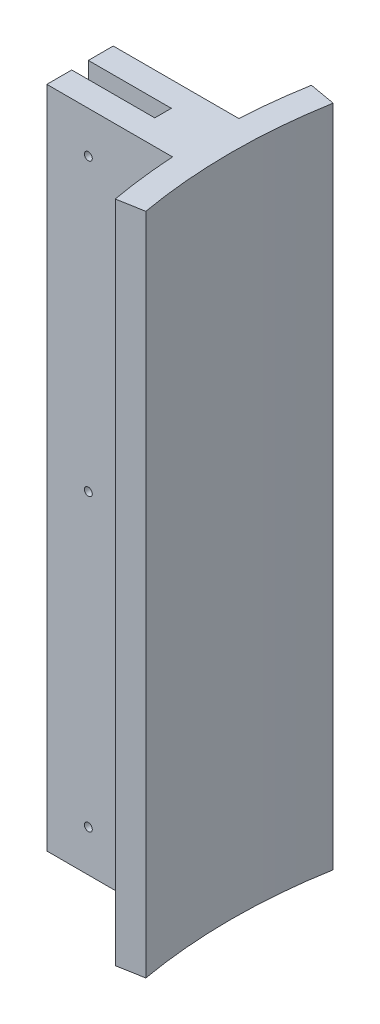
SolidWorks part; units mm, degrees
ref_plane "Front Plane" through (0, 0, 0) normal (0, 0, 1) x (1, 0, 0)
ref_plane "Top Plane" through (0, 0, 0) normal (0, 1, 0) x (1, 0, 0)
ref_plane "Right Plane" through (0, 0, 0) normal (1, 0, 0) x (0, 0, -1)
sketch "Sketch1" plane through (0, 0, 0) normal (0, 1, 0) x (1, 0, 0)
  line L0 (-65, 0) -> (0, 0) construction
  line L5 (-64.0125, -11.2871) -> (-67.1405, -11.8387)
  line L7 (0, 0) -> (-80.1235, 0) construction
  line L8 (-68.2228, -4) -> (-68.0775, -4)
  line L11 (-68.2228, -4) -> (-83.2228, -4)
  line L12 (-83.2228, 4) -> (-83.2228, 1)
  line L13 (-68.2228, 4) -> (-68.0937, 4)
  line L14 (-68.2228, 4) -> (-83.2228, 4)
  line L15 (-83.2228, 1) -> (-73.2228, 1)
  line L16 (-83.2228, -1) -> (-73.2228, -1)
  line L17 (-73.2228, -1) -> (-73.2228, 1)
  line L18 (-83.2228, -1) -> (-83.2228, -4)
  line L20 (-64.0125, 11.2871) -> (-67.1878, 11.847)
  arc A0 (-64.0125, -11.2871) -> (-64.0125, 11.2871) centre (0, 0) cw
  arc A3 (-67.1405, -11.8387) -> (-68.0775, -4) centre (-0.2035, 0.1379) cw
  arc A4 (-68.0937, 4) -> (-67.1878, 11.847) centre (-0.2035, 0.1379) cw
  point P4 (-65, 0)
  point P20 (-68.0775, -4)
  point P21 (-68.0937, 4)
  point P22 (0, 0)
  point P23 (0, 0)
  point P24 (0, 0)
  point P25 (0, 0)
  dimension "D1" = 15
  dimension "D2" = 10
extrude "Boss-Extrude1" add sketch "Sketch1" along normal blind 80
sketch "Sketch9" plane through (0, 0, 4) normal (0, 0, 1) x (1, 0, 0)
  line L0 (-78.2228, 80) -> (-78.2228, 0) construction
  line L1 (-83.2228, 80) -> (-68.0775, 80) construction
  line L2 (-78.2228, 75) -> (-83.2228, 75) construction
  line L3 (-78.2228, 40) -> (-83.2228, 40) construction
  line L4 (-78.2228, 5) -> (-83.2228, 5) construction
  line L5 (-83.2228, 0) -> (-68.0775, 0) construction
  line L6 (-83.2228, 80) -> (-83.2228, 0) construction
  dimension "D1" = 80
  dimension "D2" = 5
  dimension "D3" = 5
  dimension "D4" = 5
hole_wizard "M1.2x0.25 Tapped Hole2" positions "Sketch10" profile "Sketch11" tap size "M1.2x0.25" standard "ANSI Metric" end condition through all
sketch "Sketch10" plane through (0, 0, 4) normal (0, 0, 1) x (1, 0, 0)
  point P0 (-78.2228, 75)
  point P3 (-78.2228, 40)
  point P7 (-78.2228, 5)
sketch "Sketch11" plane through (-78.2228, 75, 4) normal (1, 0, 0) x (0, -1, 0)
  line L0 (0, 0) -> (0, 15.847)
  line L1 (0, 15.847) -> (0.475, 15.847)
  line L2 (0.475, 15.847) -> (0.475, 0)
  line L5 (0.475, 0) -> (0, 0)
  line L11 (0, -6.35) -> (0, 107.95) construction
  dimension "Thru Tap Drill Dia." = 0.95
  dimension "Thru Tap Drill Depth" = 15.847
cosmetic thread "Hole Thread4" parameters "D2"=1.2
cosmetic thread "Hole Thread5" parameters "D2"=1.2
cosmetic thread "Hole Thread6" parameters "D2"=1.2
